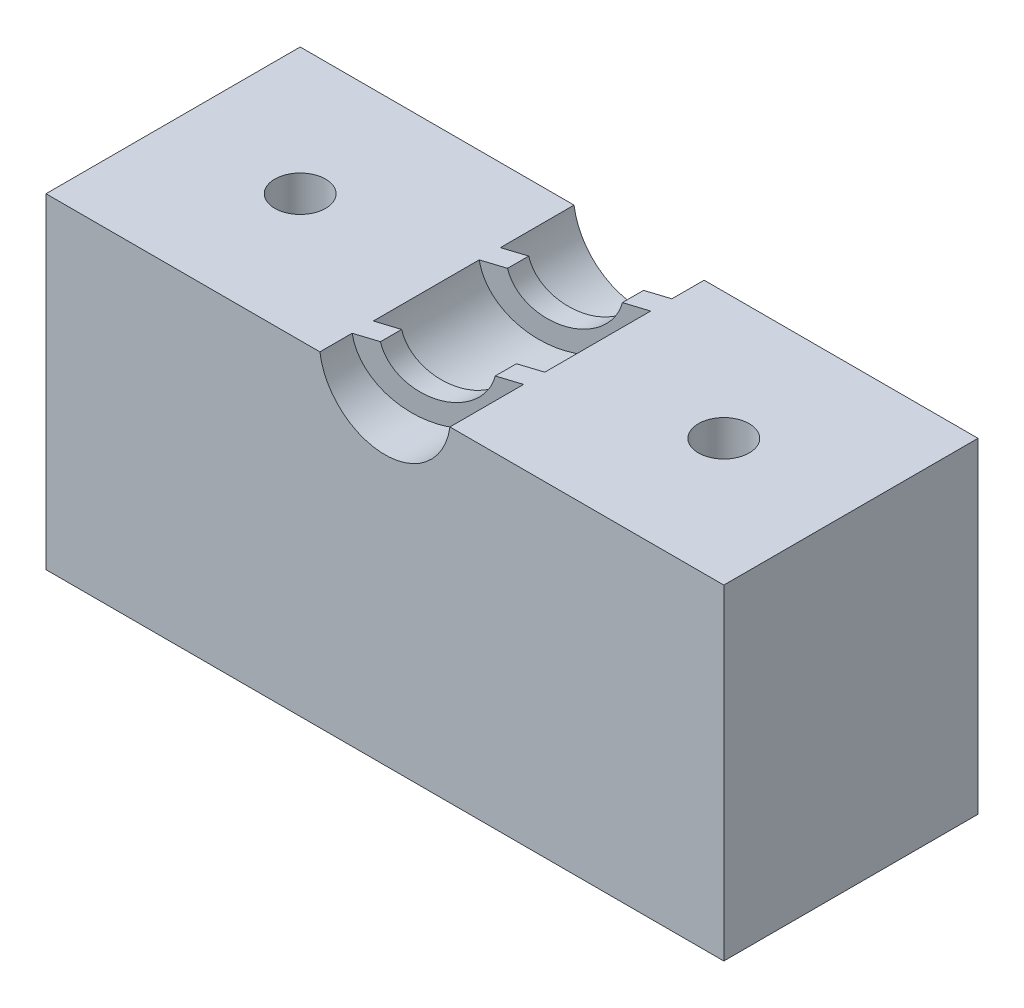
SolidWorks part; units mm, degrees
ref_plane "前视基准面" through (0, 0, 0) normal (0, 0, 1) x (1, 0, 0)
ref_plane "上视基准面" through (0, 0, 0) normal (0, 1, 0) x (1, 0, 0)
ref_plane "右视基准面" through (0, 0, 0) normal (1, 0, 0) x (0, 0, -1)
other "Configuration Table"
sketch "草图1" plane through (0, 0, 0) normal (0, 0, 1) x (1, 0, 0)
  line L1 (-8, -8) -> (8, -8)
  line L2 (-8, -8) -> (-8, 8)
  line L3 (-8, 8) -> (8, 8)
  line L4 (8, -8) -> (8, 8)
  line L5 (-8, -8) -> (8, 8) construction
  line L6 (-8, 8) -> (8, -8) construction
  circle A0 centre (0, 0) radius 1.55
  point P0 (0, 0)
  dimension "D3" = 3.1
  dimension "D1" = 16
  dimension "D2" = 16
extrude "凸台-拉伸1" add sketch "草图1" along normal mid plane 6
sketch "草图6" plane through (0, 0, 0) normal (0, 1, 0) x (1, 0, 0)
  line L0 (-1.55, -3) -> (1.55, -3) construction
  line L1 (1.55, 3) -> (-1.55, 3) construction
  line L2 (-1.55, -3) -> (1.55, -3)
  line L3 (1.55, 3) -> (-1.55, 3)
  line L4 (-1.55, 3) -> (-1.55, -3)
  line L5 (1.55, -3) -> (1.55, 3)
  line L6 (-1.55, 0.7565) -> (1.55, 1.7435)
  line L7 (1.55, 1.7435) -> (1.55, 2.2435)
  line L8 (1.55, 2.2435) -> (-1.55, 1.2565)
  line L9 (-1.55, -1.7435) -> (1.55, -0.7565)
  line L10 (-1.55, -2.2435) -> (1.55, -1.2565)
  line L11 (-2.0945, -0.6668) -> (3.135, 0.9981) construction
  line L12 (-3.1004, 0) -> (4.2723, 0) construction
  dimension "D1" = 2.5
  dimension "D2" = 0.5
  dimension "D3" = 0.5
  dimension "D4" = 17.66
extrude "凸台-拉伸2" add sketch "草图6" against normal up to surface (8 mm away) contours L4 L10 L5 L9 | L5 L8 L4 L6 up to face at (0, -8, 0)
sketch "草图7" plane through (0, 0, 0) normal (0, 0, 1) x (1, 0, 0)
  line L0 (0, 0) -> (-1.0279, -0.2141)
  line L1 (0, 0) -> (1.0279, -0.2141)
  line L2 (-1.0279, -0.2141) -> (-8, -0.2141)
  line L3 (1.0279, -0.2141) -> (8, -0.2141)
  line L6 (8, -8) -> (8, 8)
  line L7 (-8, -8) -> (8, -8)
  line L8 (-8, 8) -> (-8, -8)
  line L9 (8, 8) -> (-8, 8)
  line L10 (8, -8) -> (8, 8)
  line L11 (-8, -8) -> (8, -8)
  line L12 (-8, 8) -> (-8, -8)
  line L13 (8, 8) -> (-8, 8)
  circle A0 centre (0, 0) radius 1.05
  dimension "D1" = 2.1
  dimension "D2" = 0
  dimension "D3" = 156.47
extrude "切除-拉伸2" cut sketch "草图7" against normal through all both and the other way through all contours A0 L3 L10 L13 L12 L2 | L1 A0 L0 | L0 A0 L1
sketch "草图8" plane through (0, 0, 0) normal (0, 1, 0) x (1, 0, 0)
  line L0 (0, 5.5834) -> (0, -5.0797) construction
  circle A0 centre (-5, 0) radius 0.6
  circle A1 centre (5, 0) radius 0.6
  dimension "D2" = 1.2
  dimension "D3" = 10
extrude "切除-拉伸3" cut sketch "草图8" against normal through all
sketch "草图10" plane through (0, -8, 0) normal (0, -1, 0) x (1, 0, 0)
  line L4 (-8, -3) -> (8, -3)
  line L5 (8, -3) -> (8, 3)
  line L6 (8, 3) -> (-8, 3)
  line L7 (-8, 3) -> (-8, -3)
  line L8 (-8, -3) -> (8, -3)
  line L9 (8, -3) -> (8, 3)
  line L10 (8, 3) -> (-8, 3)
  line L11 (-8, 3) -> (-8, -3)
  circle A0 centre (-5, 0) radius 0.6 construction
  circle A1 centre (5, 0) radius 0.6 construction
  circle A2 centre (-5, 0) radius 0.6
  circle A3 centre (5, 0) radius 0.6
  dimension "D1" = 0
extrude "切除-拉伸7" cut sketch "草图10" against normal blind 0.1
equation "\"x\"=0.8094"
